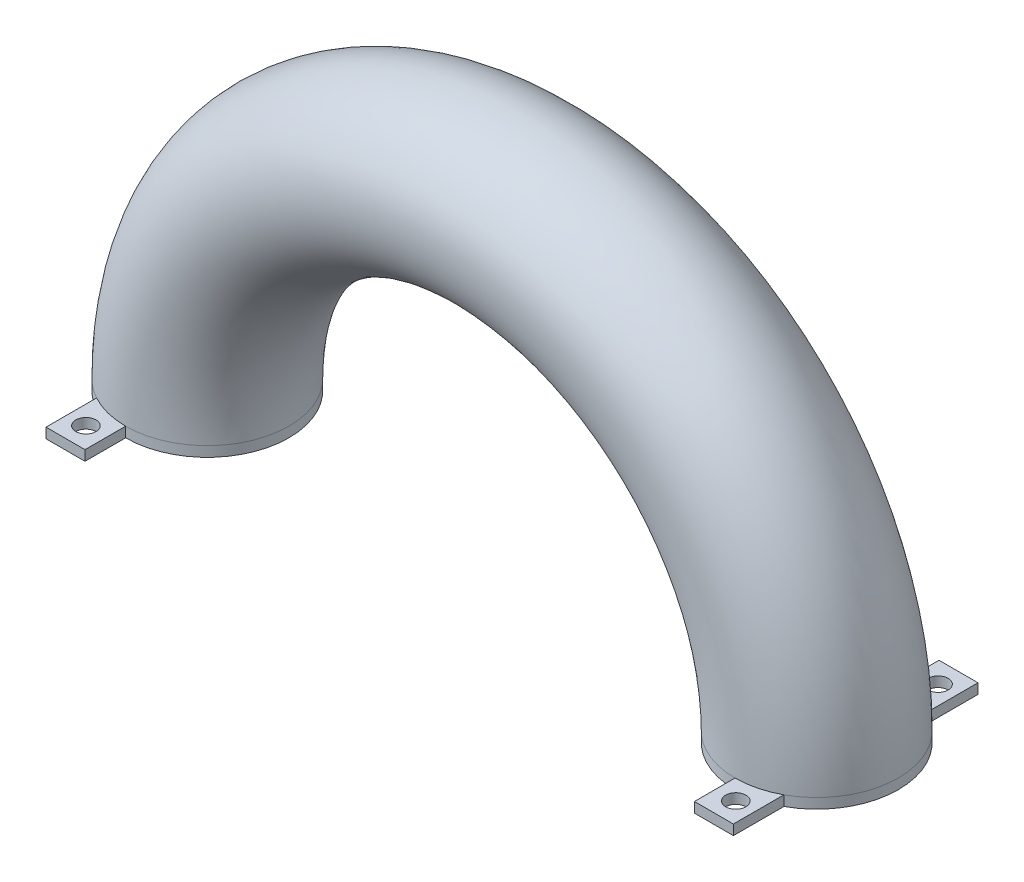
SolidWorks part; units mm, degrees
ref_plane "Płaszczyzna przednia" through (0, 0, 0) normal (0, 0, 1) x (1, 0, 0)
ref_plane "Płaszczyzna górna" through (0, 0, 0) normal (0, 1, 0) x (1, 0, 0)
ref_plane "Płaszczyzna prawa" through (0, 0, 0) normal (1, 0, 0) x (0, 0, -1)
sketch "Sketch1" plane through (0, 0, 0) normal (0, 0, 1) x (1, 0, 0)
  arc A0 (60.25, 0) -> (-60.25, 0) centre (0, 0) ccw
  point P4 (0, 0)
  dimension "D1" = 120.5
ref_plane "Plane1" through (-60.25, 0, 0) normal (0, -1, 0) x (-1, 0, 0)
ref_plane "Plane2" through (60.25, 0, 0) normal (0, 1, 0) x (1, 0, 0)
sketch "Sketch21" plane through (60.25, 0, 0) normal (0, 1, 0) x (1, 0, 0)
  line L0 (-120.5, 0) -> (0, 0) construction
  line L1 (0, -1000) -> (0, 49000) construction
  circle A0 centre (0, 0) radius 14.15
  circle A1 centre (0, 0) radius 16.15
  dimension "D1" = 28.3
  dimension "D2" = 2
sweep "Sweep2" add profiles "Sketch21" path "Sketch1"
sketch "Sketch25" plane through (-60.25, 0, 0) normal (0, -1, 0) x (-1, 0, 0)
  line L0 (-120.5, 0) -> (0, 0) construction
  line L1 (0, 28.283) -> (0, -31.004) construction
  line L2 (44.5067, 0) -> (-37.663, 0) construction
  line L3 (0, -15.0256) -> (7.7097, -13.2502)
  line L4 (0, 15.0256) -> (7.7097, 13.2502)
  line L5 (0, 15.0256) -> (0, 24.1837)
  line L6 (0, 24.1837) -> (7.7097, 24.1837)
  line L7 (7.7097, 13.2502) -> (7.7097, 24.1837)
  line L8 (7.7097, -13.2502) -> (7.7097, -24.1837)
  line L9 (0, -15.0256) -> (0, -24.1837)
  line L10 (0, -24.1837) -> (7.7097, -24.1837)
  circle A0 centre (0, 0) radius 14.15
  circle A1 centre (0, 0) radius 16.15
  circle A2 centre (4, 20) radius 2
  circle A3 centre (4, -20) radius 2
  point P13 (0, 0)
  point P14 (7.7097, 13.2502)
  dimension "D1" = 4
  dimension "D2" = 20
  dimension "D3" = 4
extrude "Boss-Extrude3" add sketch "Sketch25" along normal blind 2 contours A1 L7 L6 L5 A2 | A1 L9 L10 L8 A3 | A0
mirror "Mirror3" about plane through (0, 0, 0) normal (1, 0, 0) of "Boss-Extrude3"
